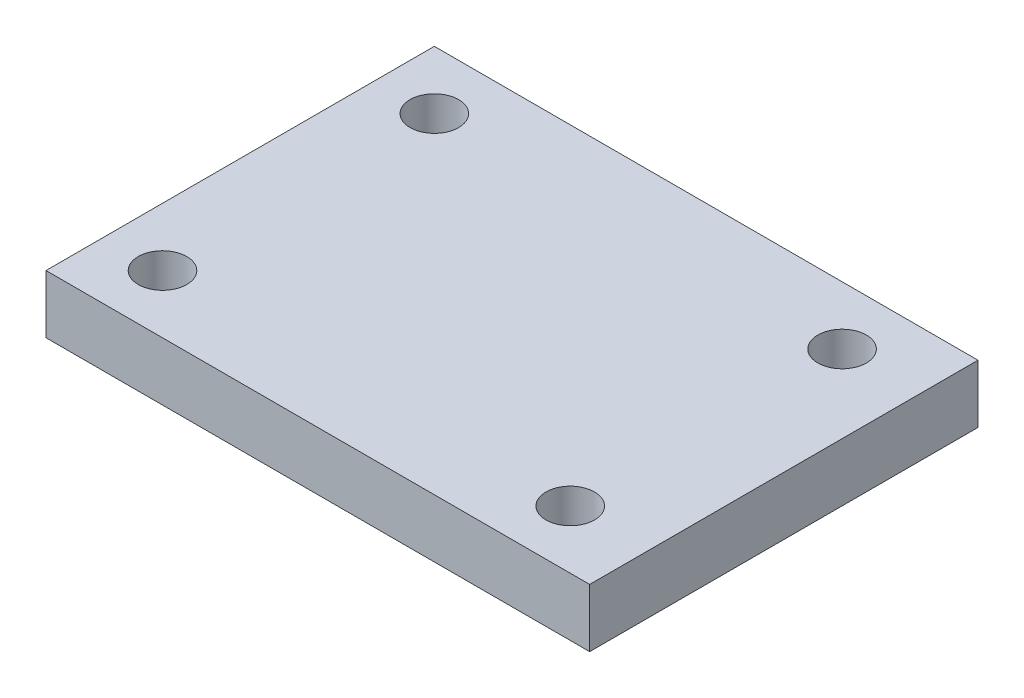
SolidWorks part; units mm, degrees
ref_plane "Front Plane" through (0, 0, 0) normal (0, 0, 1) x (1, 0, 0)
ref_plane "Top Plane" through (0, 0, 0) normal (0, 1, 0) x (1, 0, 0)
ref_plane "Right Plane" through (0, 0, 0) normal (1, 0, 0) x (0, 0, -1)
sketch "Sketch1" plane through (0, 0, 0) normal (0, 1, 0) x (1, 0, 0)
  line L1 (-14, 10) -> (14, 10)
  line L2 (-14, 10) -> (-14, -10)
  line L3 (-14, -10) -> (14, -10)
  line L4 (14, 10) -> (14, -10)
  point P0 (0, 0)
  point P6 (-14, -7)
  point P7 (14, -7)
  point P8 (-14, 7)
  point P9 (14, 7)
  point P10 (-11, 10)
  point P11 (-11, -10)
  point P12 (11, 10)
  point P13 (11, -10)
  dimension "D1" = 28
  dimension "D2" = 14
  dimension "D3" = 20
  dimension "D4" = 10
extrude "Boss-Extrude1" add sketch "Sketch1" against normal blind 3
hole_wizard "M3 Tapped Hole1" positions "Sketch2" profile "Sketch3" tap size "M3" standard "DIN" end condition through all
sketch "Sketch2" plane through (0, 0, 0) normal (0, 1, 0) x (1, 0, 0)
  line L1 (-14, 10) -> (-14, -10) construction
  line L2 (14, 10) -> (-14, 10) construction
  point P0 (-11, 7)
  point P2 (-11, -7)
  point P4 (10, 7)
  point P6 (10, -7)
  dimension "D1" = 14
  dimension "D2" = 3
  dimension "D3" = 3
  dimension "D4" = 21
sketch "Sketch3" plane through (-11, 0, -7) normal (1, 0, 0) x (0, 0, 1)
  line L0 (0, 0) -> (0, 3)
  line L1 (0, 3) -> (1.25, 3)
  line L2 (1.25, 3) -> (1.25, 0)
  line L5 (1.25, 0) -> (0, 0)
  line L11 (0, -6.35) -> (0, 107.95) construction
  dimension "Thru Tap Drill Dia." = 2.5
  dimension "Thru Tap Drill Depth" = 3
cosmetic thread "Hole Thread1"
cosmetic thread "Hole Thread2"
cosmetic thread "Hole Thread3"
cosmetic thread "Hole Thread4"
